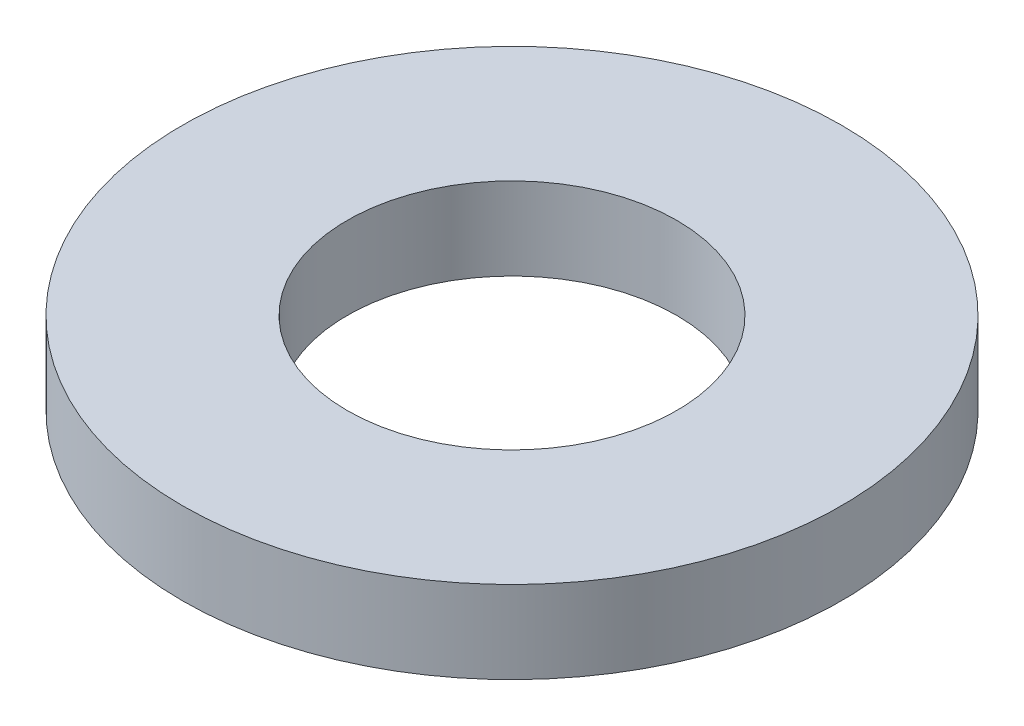
SolidWorks part; units mm, degrees
ref_plane "Front Plane" through (0, 0, 0) normal (0, 0, 1) x (1, 0, 0)
ref_plane "Top Plane" through (0, 0, 0) normal (0, 1, 0) x (1, 0, 0)
ref_plane "Right Plane" through (0, 0, 0) normal (1, 0, 0) x (0, 0, -1)
sketch "Sketch1" plane through (0, 0, 0) normal (0, 1, 0) x (1, 0, 0)
  circle A0 centre (0, 0) radius 6.35
  dimension "D1" = 12.7
extrude "Boss-Extrude1" add sketch "Sketch1" along normal blind 1.5875
sketch "Sketch2" plane through (0, 1.5875, 0) normal (0, 1, 0) x (1, 0, 0)
  circle A0 centre (0, 0) radius 3.175
  dimension "D1" = 6.35
extrude "Cut-Extrude1" cut sketch "Sketch2" against normal blind 17.4625
